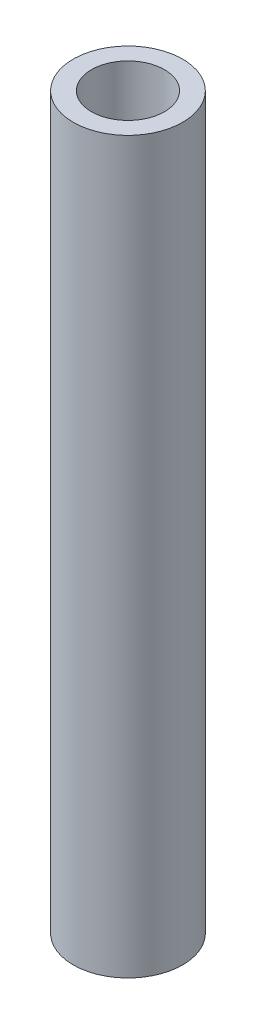
SolidWorks part; units mm, degrees
material "POLYURETHANE (11671)"
ref_plane "Front Plane" through (0, 0, 0) normal (0, 0, 1) x (1, 0, 0)
ref_plane "Top Plane" through (0, 0, 0) normal (0, 1, 0) x (1, 0, 0)
ref_plane "Right Plane" through (0, 0, 0) normal (1, 0, 0) x (0, 0, -1)
sketch "Sketch4" plane through (0, 0, 0) normal (0, 1, 0) x (1, 0, 0)
  circle A0 centre (0, 0) radius 5
  circle A1 centre (0, 0) radius 7.5
  dimension "D1" = 10
  dimension "D2" = 15
sketch "Sketch5" plane through (0, 0, 0) normal (0, 0, 1) x (1, 0, 0)
  spline S0 degree 2 poles (0, 0) (0, 50) (0, 100) knots 0 0 0 1 1 1
  point P2 (0, 0)
sweep "Sweep1" add profiles "Sketch4" path "Sketch5"
